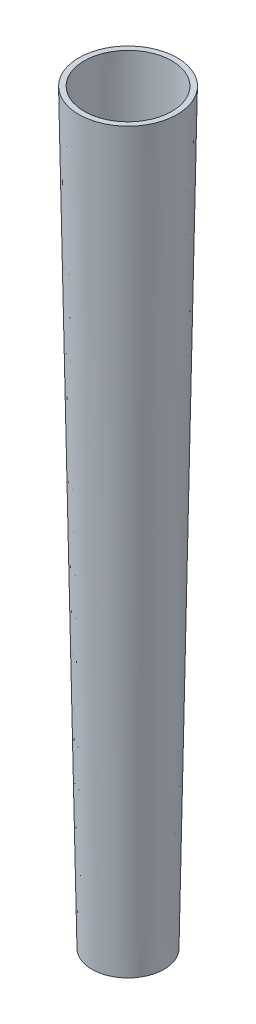
SolidWorks part; units mm, degrees
ref_plane "Front Plane" through (0, 0, 0) normal (0, 0, 1) x (1, 0, 0)
ref_plane "Top Plane" through (0, 0, 0) normal (0, 1, 0) x (1, 0, 0)
ref_plane "Right Plane" through (0, 0, 0) normal (1, 0, 0) x (0, 0, -1)
sketch "Sketch1" plane through (0, 0, 0) normal (0, 0, 1) x (1, 0, 0)
  line L0 (0, 0) -> (0, 140) construction
  line L1 (-2.5175, 1) -> (-4.9437, 140)
  line L2 (-123.5875, 0) -> (-19.0211, 0) construction
  line L3 (0, 140) -> (-5.9439, 140) construction
  line L4 (-5.9439, 140) -> (-3.5002, 0)
  line L5 (-3.5002, 0) -> (-2.5, 0)
  line L8 (-5.7693, 0) -> (-8.213, 140)
  line L9 (-6.7695, 0) -> (-5.7693, 0)
  line L10 (-9.2132, 140) -> (-6.7695, 0)
  line L37 (-9.0387, 0) -> (0, 0) construction
  line L38 (-8.213, 140) -> (-9.2132, 140) construction
  line L40 (-9.2132, 140) -> (-8.213, 140)
  line L42 (-5.9439, 140) -> (-4.9437, 140)
  line L46 (-2.5, 0) -> (0, 0)
  line L47 (0, 0) -> (0, 1)
  line L48 (0, 1) -> (-2.5175, 1)
  line L52 (-25.5599, 140) -> (-23.1162, 0) [skipped]
  line L53 (-22.116, 0) -> (-24.5597, 140) [skipped]
  line L54 (-23.1162, 0) -> (-22.116, 0) [skipped]
  line L55 (-19.8468, 0) -> (-18.8467, 0) [skipped]
  line L56 (-20.6716, 47.2479) -> (-19.8468, 0) [skipped]
  line L57 (-18.8467, 0) -> (-20.6716, 104.5465) [skipped]
  line L58 (-19.0212, 140) -> (-16.5775, 0) [skipped]
  line L59 (-16.5775, 0) -> (-15.5773, 0) [skipped]
  line L60 (-9.0387, 0) -> (-11.4824, 140) [skipped]
  line L61 (-10.0388, 0) -> (-9.0387, 0) [skipped]
  line L62 (-12.308, 0) -> (-14.7517, 140) [skipped]
  line L63 (-15.7519, 140) -> (-13.3082, 0) [skipped]
  line L64 (-13.3082, 0) -> (-12.308, 0) [skipped]
  line L65 (-12.4825, 140) -> (-10.0388, 0) [skipped]
  line L66 (-15.5773, 0) -> (-18.0211, 140) [skipped]
  dimension "D1" = 89
  dimension "D2" = 140
  dimension "D3" = 2.5
  dimension "D4" = 1
  dimension "D8" = 1
  dimension "D9" = 2.2692
  dimension "D5" = 7
revolve "Revolve2" add sketch "Sketch1" angle 360 about L0
sketch "Sketch2" plane through (0, 0, 0) normal (0, -1, 0) x (-1, 0, 0)
  circle A0 centre (0, 0) radius 3.5002
  circle A1 centre (0, 0) radius 3.5002 construction
extrude "Cut-Extrude1" cut sketch "Sketch2" against normal blind 161 draft 1 draft outward yes
